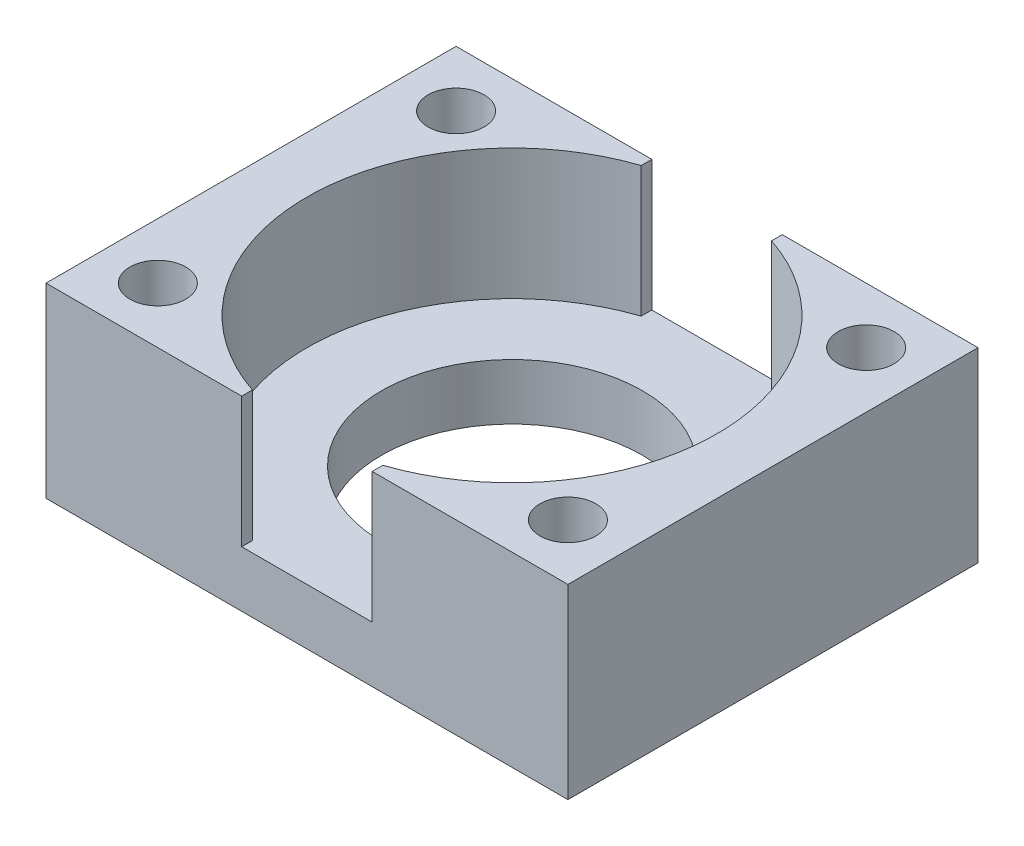
SolidWorks part; units mm, degrees
ref_plane "Front Plane" through (0, 0, 0) normal (0, 0, 1) x (1, 0, 0)
ref_plane "Top Plane" through (0, 0, 0) normal (0, 1, 0) x (1, 0, 0)
ref_plane "Right Plane" through (0, 0, 0) normal (1, 0, 0) x (0, 0, -1)
sketch "Sketch1" plane through (0, 0, 0) normal (0, 1, 0) x (1, 0, 0)
  line L1 (-14, 11) -> (14, 11)
  line L2 (-14, 11) -> (-14, -11)
  line L3 (-14, -11) -> (14, -11)
  line L4 (14, 11) -> (14, -11)
  line L5 (-14, 11) -> (14, -11) construction
  line L6 (-14, -11) -> (14, 11) construction
  point P0 (0, 0)
extrude "Boss-Extrude1" add sketch "Sketch1" along normal blind 10
sketch "Sketch2" plane through (0, 10, 0) normal (0, 1, 0) x (1, 0, 0)
  circle A0 centre (0, 0) radius 11
  point P3 (-24.8205, -6.2435)
sketch "Sketch5" plane through (0, 0, -11) normal (0, 0, -1) x (-1, 0, 0)
  line L1 (11, 10) -> (-11, 10) construction
  line L2 (-3.5, 3) -> (3.5, 3)
  line L3 (3.5, 3) -> (3.5, 10)
  line L4 (3.5, 10) -> (-3.5, 10)
  line L5 (-3.5, 3) -> (-3.5, 10)
extrude "Cut-Extrude7" cut sketch "Sketch5" against normal blind 22
extrude "Cut-Extrude8" cut sketch "Sketch2" against normal blind 7
sketch "Sketch6" plane through (0, 0, 0) normal (0, -1, 0) x (1, 0, 0)
  circle A0 centre (0, 0) radius 7
extrude "Cut-Extrude9" cut sketch "Sketch6" against normal blind 3
sketch "Sketch7" plane through (0, 0, 0) normal (0, -1, 0) x (1, 0, 0)
  circle A0 centre (11, 8) radius 1.5
  circle A1 centre (11, -8) radius 1.5
  circle A2 centre (-11, -8) radius 1.5
  circle A3 centre (-11, 8) radius 1.5
extrude "Cut-Extrude10" cut sketch "Sketch7" against normal blind 10
